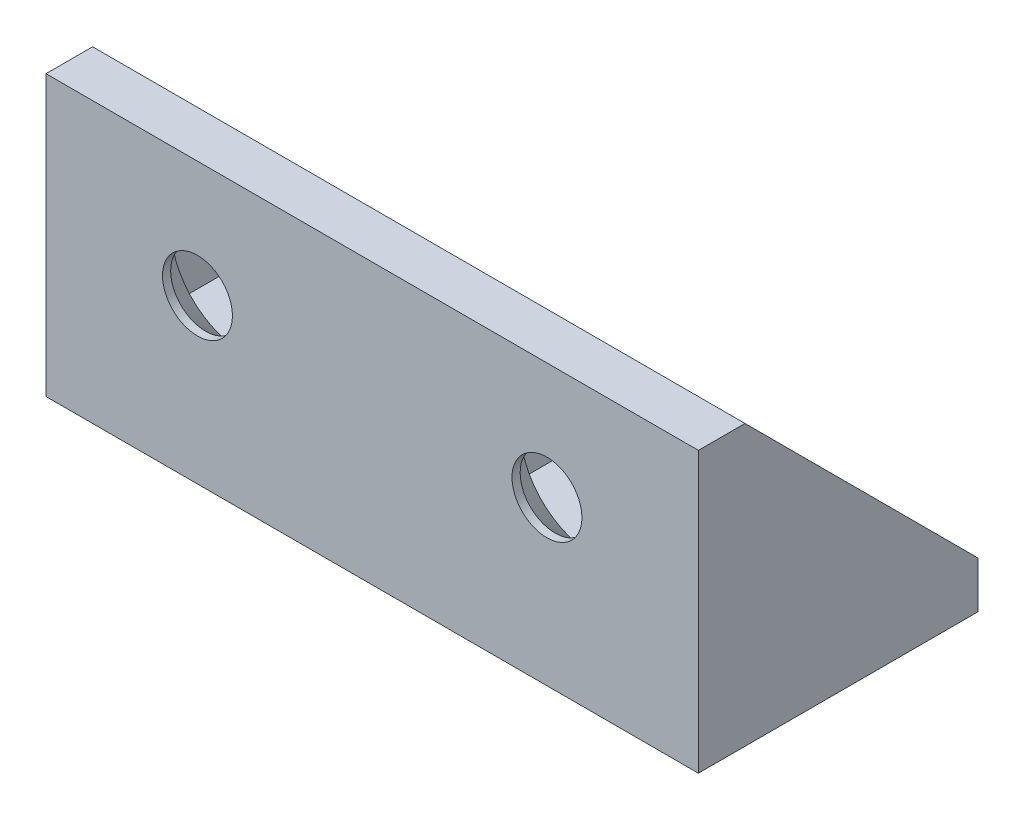
SolidWorks part; units mm, degrees
ref_plane "Alzado" through (0, 0, 0) normal (0, 0, 1) x (1, 0, 0)
ref_plane "Planta" through (0, 0, 0) normal (0, 1, 0) x (1, 0, 0)
ref_plane "Vista lateral" through (0, 0, 0) normal (1, 0, 0) x (0, 0, -1)
sketch "Croquis1" plane through (0, 0, 0) normal (0, 1, 0) x (1, 0, 0)
  line L0 (0, 10) -> (25, 10) construction
  line L1 (0, 0) -> (50, 0) construction
  line L2 (0, 0) -> (0, 20)
  line L3 (0, 20) -> (50, 20)
  line L4 (50, 0) -> (50, 20)
  line L5 (25, 10) -> (50, 10) construction
  line L6 (25, 10) -> (25, 20) construction
  line L7 (10, 12.5) -> (40, 12.5) construction
  line L8 (0, 0) -> (50, 0) construction
  line L9 (0, 0) -> (0, -4)
  line L10 (0, -4) -> (50, -4)
  line L11 (50, 0) -> (50, -4)
  circle A0 centre (10, 10) radius 2.5
  circle A1 centre (40, 10) radius 2.5
  point P15 (25, 12.5)
  point P16 (40, 6.5561)
  point P19 (0, 0)
  dimension "D3" = 5
  dimension "D1" = 50
  dimension "D2" = 20
  dimension "D4" = 4
  dimension "D5" = 30
extrude "Saliente-Extruir1" add sketch "Croquis1" along normal blind 4
sketch "Croquis2" plane through (0, 4, 0) normal (0, 1, 0) x (1, 0, 0)
  line L0 (50, -4) -> (50, 20) construction
  line L1 (0, -4) -> (50, -4)
  line L2 (0, -4) -> (0, 0)
  line L3 (0, 0) -> (50, 0)
  line L4 (50, -4) -> (50, 0)
extrude "Saliente-Extruir2" add sketch "Croquis2" along normal blind 20
sketch "Croquis3" plane through (0, 0, 0) normal (-1, 0, 0) x (0, 0, 1)
  line L0 (-20, 4) -> (-20, 0) construction
  line L1 (0, 24) -> (4, 24) construction
  line L2 (4, 24) -> (4, 0) construction
  line L3 (-20, 0) -> (4, 0) construction
  line L4 (-20, 4) -> (-20, 0)
  line L5 (0, 24) -> (4, 24)
  line L6 (4, 24) -> (4, 0)
  line L7 (-20, 0) -> (4, 0)
  line L8 (-20, 4) -> (0, 24)
extrude "Saliente-Extruir3" add sketch "Croquis3" along normal blind 3 and the other way blind 53
sketch "Croquis4" plane through (0, 0, -20) normal (0, 0, -1) x (-1, 0, 0)
  line L0 (-25, 0) -> (-25, 24) construction
  line L1 (-53, 0) -> (3, 0) construction
  line L2 (-53, 24) -> (3, 24) construction
  line L3 (-50.5, 24) -> (-50.5, 4)
  line L4 (-53, 4) -> (3, 4) construction
  line L5 (0.5, 4) -> (0.5, 24)
  line L6 (0.5, 14) -> (3, 14) construction
  line L7 (3, 24) -> (3, 4) construction
  line L8 (-50.5, 14) -> (-53, 14) construction
  line L9 (-53, 24) -> (-53, 4) construction
  line L10 (-27.5, 4) -> (-27.5, 24)
  line L11 (-22.5, 24) -> (-22.5, 4)
  line L12 (-27.5, 14) -> (-25, 14) construction
  line L13 (-25, 14) -> (-22.5, 14) construction
  line L14 (-39, 24) -> (-39, 4) construction
  line L15 (-45, 4) -> (-33, 4) construction
  line L16 (-45, 4) -> (-45, 24) construction
  line L17 (-45, 24) -> (-33, 24) construction
  line L18 (-33, 4) -> (-33, 24) construction
  line L19 (-53, 14) -> (-39, 14) construction
  line L20 (-39, 14) -> (-25, 14) construction
  line L21 (-50.5, 24) -> (-27.5, 24)
  line L22 (-50.5, 4) -> (-27.5, 4)
  line L23 (-22.5, 24) -> (0.5, 24)
  line L24 (-22.5, 4) -> (0.5, 4)
  line L25 (-45, 19.4235) -> (-50.5, 19.4235) construction
  line L26 (-33, 19.4235) -> (-27.5, 19.4235) construction
  dimension "D1" = 5
  dimension "D2" = 12
extrude "Cortar-Extruir1" cut sketch "Croquis4" against normal up to vertex (20 mm away)
sketch "Croquis5" plane through (0, 0, 0) normal (0, 0, -1) x (-1, 0, 0)
  line L0 (-40, 14) -> (-10, 14) construction
  line L1 (-25, 24) -> (-25, 4) construction
  line L2 (-27.5, 24) -> (-22.5, 24) construction
  line L3 (-27.5, 4) -> (-22.5, 4) construction
  line L4 (-10, 14) -> (3, 14) construction
  line L5 (3, 24) -> (3, 4) construction
  circle A0 centre (-40, 14) radius 3
  circle A1 centre (-10, 14) radius 3
  point P0 (-10.548, 14)
  dimension "D1" = 6
  dimension "D2" = 30
extrude "Cortar-Extruir2" cut sketch "Croquis5" against normal blind 17
sketch "Croquis6" plane through (0, 4, 0) normal (0, 1, 0) x (1, 0, 0)
  line L0 (-0.5, 10) -> (50.5, 10) construction
  line L1 (25, 0) -> (25, 20) construction
  line L2 (27.5, 0) -> (22.5, 0) construction
  line L3 (27.5, 20) -> (22.5, 20) construction
  line L4 (-0.5, 0) -> (-0.5, 20) construction
  line L5 (50.5, 0) -> (50.5, 20) construction
  line L6 (10, 12.5) -> (40, 12.5) construction
  circle A2 centre (10, 10) radius 2.5
  circle A3 centre (40, 10) radius 2.5
  point P20 (42.1057, 10)
  point P21 (25, 12.5)
  dimension "D1" = 5
  dimension "D2" = 30
extrude "Cortar-Extruir3" cut sketch "Croquis6" against normal blind 20
ref_plane "Plano1" through (0, 0, -10) normal (0, 0, 1) x (1, 0, 0)
sketch "Croquis7" plane through (0, 0, -10) normal (0, 0, 1) x (1, 0, 0)
  line L0 (40, 0.7) -> (37.5, 0.7)
  line L1 (42.5, 0) -> (42.5, 4) construction
  line L3 (50.5, 4) -> (27.5, 4) construction
  line L5 (40, 4) -> (34.2, 4)
  line L6 (34.2, 4) -> (37.5, 0.7)
  line L7 (40, 0.7) -> (40, 4)
  line L8 (42.5, 2) -> (37.5, 2) construction
  line L10 (37.5, 4) -> (37.5, 0) construction
  point P3 (36.5632, 0.7)
  point P4 (0, 0)
  point P12 (40, 2)
  point P13 (0, 0)
  point P16 (0, 0)
  point P17 (0, 0)
  dimension "D1" = 3.3
  dimension "D2" = 45
revolve "Cortar-Revolución1" cut sketch "Croquis7" angle 360 about L7
sketch "Croquis8" plane through (0, 0, -10) normal (0, 0, 1) x (1, 0, 0)
  line L0 (10, 4) -> (10, 0.7)
  line L1 (22.5, 4) -> (-0.5, 4) construction
  line L2 (10, 0.7) -> (12.5, 0.7)
  line L4 (12.5, 0.7) -> (15.8, 4)
  line L5 (15.8, 4) -> (10, 4)
  line L6 (12.5, 0) -> (12.5, 4) construction
  line L7 (7.5, 2) -> (12.5, 2) construction
  line L8 (7.5, 4) -> (7.5, 0) construction
  point P4 (10, 2)
  dimension "D1" = 3.3
  dimension "D2" = 45
revolve "Cortar-Revolución2" cut sketch "Croquis8" angle 360 about L0
ref_plane "Plano2" through (0, 14, 0) normal (0, 1, 0) x (1, 0, 0)
sketch "Croquis9" plane through (0, 14, 0) normal (0, 1, 0) x (1, 0, 0)
  line L0 (40, 0) -> (40, -3.3)
  line L1 (27.5, 0) -> (50.5, 0) construction
  line L2 (40, -3.3) -> (43, -3.3)
  line L3 (43, -4) -> (43, 0) construction
  line L4 (43, -3.3) -> (46.3, 0)
  line L5 (46.3, 0) -> (40, 0)
  line L6 (37, -2) -> (43, -2) construction
  line L7 (37, 0) -> (37, -4) construction
  point P4 (40, -2)
  dimension "D1" = 3.3
  dimension "D2" = 45
revolve "Cortar-Revolución3" cut sketch "Croquis9" angle 360 about L0
sketch "Croquis10" plane through (0, 14, 0) normal (0, 1, 0) x (1, 0, 0)
  line L0 (10, 0) -> (10, -3.3)
  line L1 (-0.5, 0) -> (22.5, 0) construction
  line L2 (10, -3.3) -> (13, -3.3)
  line L3 (13, -4) -> (13, 0) construction
  line L4 (13, -3.3) -> (16.3, 0)
  line L5 (16.3, 0) -> (10, 0)
  line L6 (7, -2) -> (13, -2) construction
  line L7 (7, 0) -> (7, -4) construction
  point P12 (10, -2)
  dimension "D1" = 3.3
  dimension "D2" = 45
revolve "Cortar-Revolución4" cut sketch "Croquis10" angle 360 about L0
